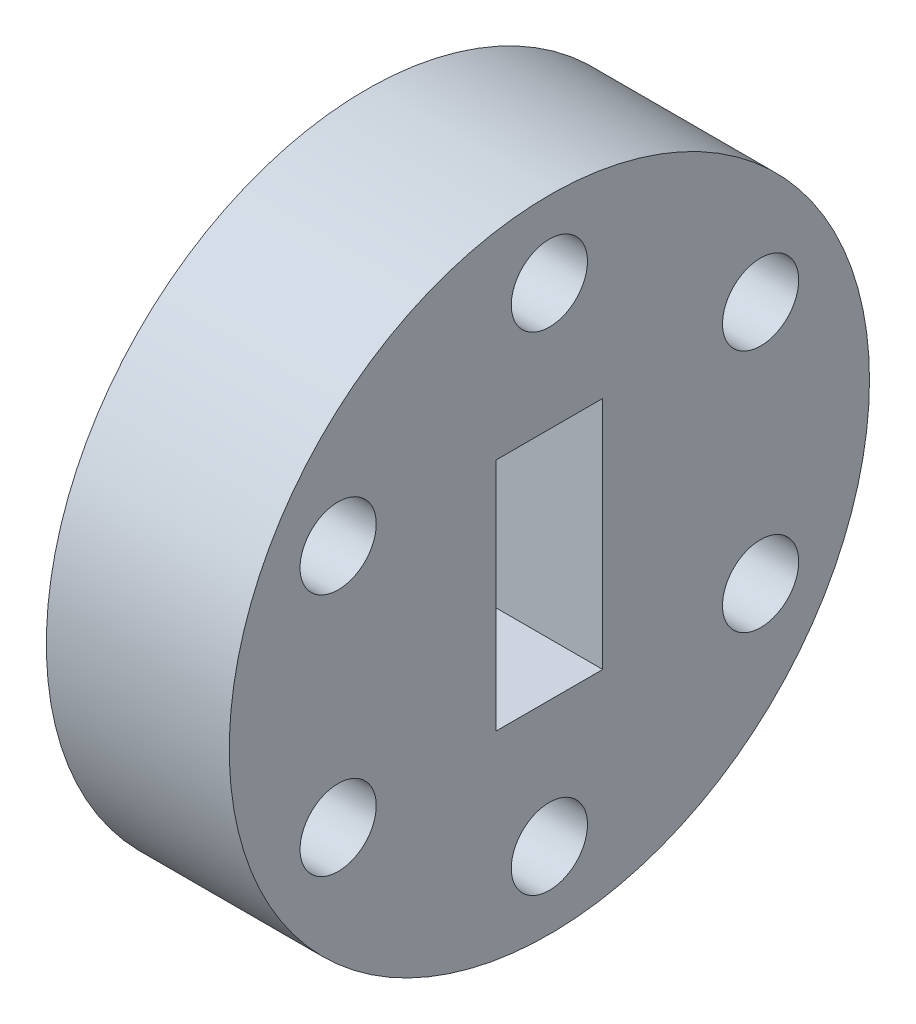
SolidWorks part; units mm, degrees
ref_plane "Front Plane" through (0, 0, 0) normal (0, 0, 1) x (1, 0, 0)
ref_plane "Top Plane" through (0, 0, 0) normal (0, 1, 0) x (1, 0, 0)
ref_plane "Right Plane" through (0, 0, 0) normal (1, 0, 0) x (0, 0, -1)
sketch "Sketch1" plane through (0, 0, 0) normal (1, 0, 0) x (0, 0, -1)
  circle A0 centre (0, 0) radius 10.5
  dimension "D1" = 21
extrude "Boss-Extrude1" add sketch "Sketch1" along normal blind 6
sketch "Sketch2" plane through (6, 0, 0) normal (1, 0, 0) x (0, 0, -1)
  circle A0 centre (0, 8) radius 1.25
  circle A1 centre (6.9282, 4) radius 1.25
  circle A2 centre (6.9282, -4) radius 1.25
  circle A3 centre (0, -8) radius 1.25
  circle A4 centre (-6.9282, -4) radius 1.25
  circle A5 centre (-6.9282, 4) radius 1.25
  point P12 (0, 0)
  dimension "D1" = 8
  dimension "D2" = 2.5
  dimension "D3" = 6
extrude "Cut-Extrude1" cut sketch "Sketch2" against normal through all
sketch "Sketch3" plane through (6, 0, 0) normal (1, 0, 0) x (0, 0, -1)
  line L1 (-1.75, 3.85) -> (1.75, 3.85)
  line L2 (-1.75, 3.85) -> (-1.75, -3.85)
  line L3 (-1.75, -3.85) -> (1.75, -3.85)
  line L4 (1.75, 3.85) -> (1.75, -3.85)
  line L5 (-1.75, 3.85) -> (1.75, -3.85) construction
  line L6 (-1.75, -3.85) -> (1.75, 3.85) construction
  point P0 (0, 0)
  dimension "D1" = 7.7
  dimension "D2" = 3.5
extrude "Cut-Extrude2" cut sketch "Sketch3" against normal blind 6
